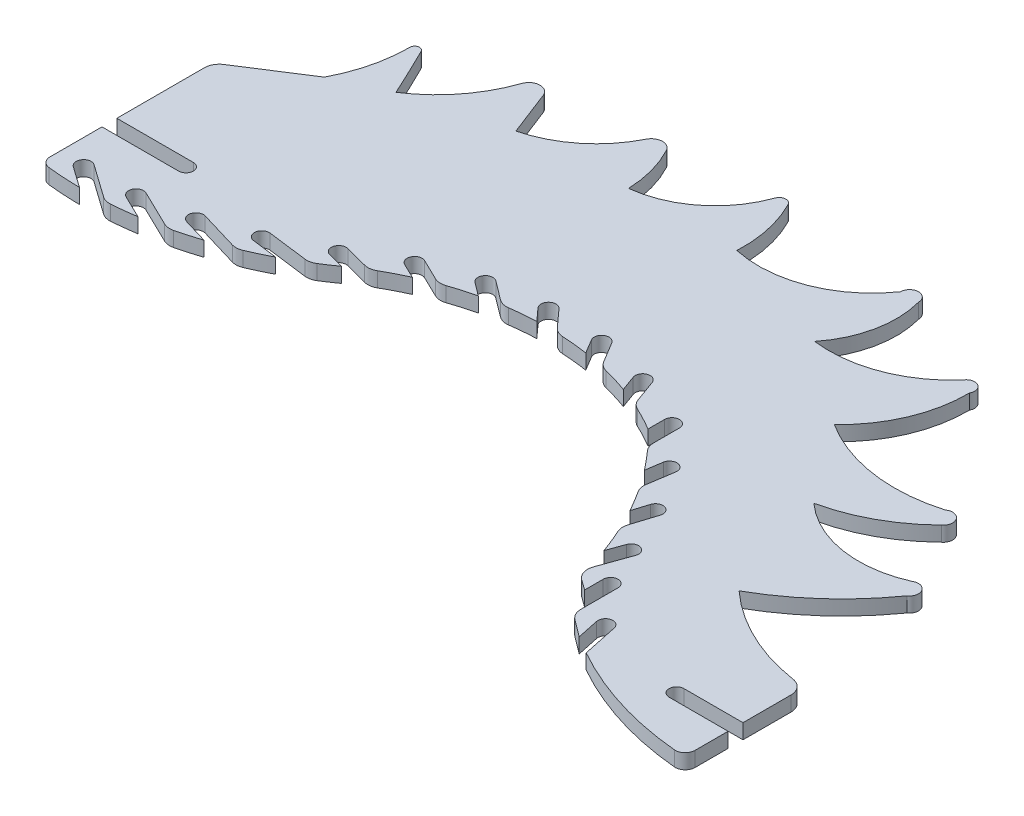
SolidWorks part; units mm, degrees
ref_plane "Front Plane" through (0, 0, 0) normal (0, 0, 1) x (1, 0, 0)
ref_plane "Top Plane" through (0, 0, 0) normal (0, 1, 0) x (1, 0, 0)
ref_plane "Right Plane" through (0, 0, 0) normal (1, 0, 0) x (0, 0, -1)
sketch "Sketch1" plane through (0, 0, 0) normal (0, 1, 0) x (1, 0, 0)
  line L0 (0, 0) -> (-11.9, 0)
  line L1 (-11.9, -3) -> (0, -3)
  line L2 (0, -3) -> (0, -11.81)
  line L3 (0, 0) -> (0, 12.34)
  line L4 (-28, -3.62) -> (-29.5212, 3.5443)
  line L5 (-32.4557, 2.9212) -> (-31.5128, -1.52)
  line L6 (-31.5128, -1.52) -> (-36.1543, 1.95)
  line L7 (-36.1543, 1.95) -> (-36.1543, 10.96)
  line L8 (-39.1543, 10.96) -> (-39.1543, 7.21)
  line L9 (-39.1543, 7.21) -> (-43.0543, 10.02)
  line L10 (-43.0543, 10.02) -> (-40.0457, 18.3911)
  line L11 (-42.8689, 19.4057) -> (-44.0821, 16.03)
  line L12 (-60.88, 41.7175) -> (-60.88, 45.0575)
  line L13 (-57.88, 45.0575) -> (-57.88, 38.6806)
  line L14 (-50.5732, 36.9998) -> (-51.5447, 30.6973)
  line L15 (-54.0471, 34.1558) -> (-53.5382, 37.4568)
  line L16 (-44.5793, 27.923) -> (-46.4997, 21.8421)
  line L17 (-48.4459, 25.6414) -> (-47.4401, 28.8264)
  line L18 (-68.5978, 50.2986) -> (-66.54, 44.6449)
  line L19 (-70.2786, 46.1451) -> (-71.4169, 49.2725)
  line L20 (-80.4271, 48.716) -> (-82.1438, 51.5672)
  line L21 (-79.5737, 53.1147) -> (-76.4703, 47.9603)
  line L22 (-90.8803, 49.2938) -> (-93.1117, 51.7631)
  line L23 (-90.8859, 53.7745) -> (-86.8519, 49.3106)
  line L24 (-101.2503, 47.8571) -> (-103.9137, 49.8528)
  line L25 (-102.1147, 52.2536) -> (-97.2999, 48.6458)
  line L26 (-111.1527, 44.4592) -> (-114.1492, 45.9074)
  line L27 (-112.8438, 48.6085) -> (-107.4267, 45.9905)
  line L28 (-120.22, 39.2261) -> (-123.4386, 40.0729)
  line L29 (-122.6752, 42.9742) -> (-116.8567, 41.4432)
  line L30 (-160.4297, 26.5895) -> (-164.6544, 29.5786)
  line L31 (-162.9217, 32.0276) -> (-155.4197, 26.7198)
  line L32 (-149.4017, 27.3689) -> (-154.0553, 29.6332)
  line L33 (-152.7427, 32.3308) -> (-144.4792, 28.3099)
  line L34 (-138.6461, 29.9265) -> (-143.6054, 31.4061)
  line L35 (-142.7477, 34.2809) -> (-133.9414, 31.6534)
  line L36 (-128.4478, 34.1946) -> (-133.5813, 34.8503)
  line L37 (-133.2012, 37.8261) -> (-124.0854, 36.6617)
  line L38 (-168.7197, 27.1883) -> (-168.7197, 39.4283)
  line L39 (-168.7197, 39.4283) -> (-153.2697, 39.4283)
  line L40 (-153.2697, 42.4283) -> (-168.7197, 42.4283)
  line L41 (-168.7197, 42.4283) -> (-168.7197, 61.7183)
  line L42 (-168.7197, 61.7183) -> (-154.9797, 70.5483)
  line L43 (-129.7315, 89.4454) -> (-126.2359, 80.4346)
  arc A0 (-11.9, 0) -> (-11.9, -3) centre (-11.9, -1.5) ccw
  arc A1 (0, 12.34) -> (-23.42, 22.6266) centre (3.4988, 52.1101) cw
  arc A2 (0, -11.81) -> (-28, -3.62) centre (3.4988, 52.1101) cw
  arc A3 (-29.5212, 3.5443) -> (-32.4557, 2.9212) centre (-30.9885, 3.2327) ccw
  arc A4 (-36.1543, 10.96) -> (-39.1543, 10.96) centre (-37.6543, 10.96) ccw
  arc A5 (-40.0457, 18.3911) -> (-42.8689, 19.4057) centre (-41.4573, 18.8984) ccw
  arc A6 (-120.22, 39.2261) -> (-111.1527, 44.4592) centre (-88.64, -5.02) cw construction
  arc A7 (-44.0821, 16.03) -> (-60.88, 41.7175) centre (-106.8072, -6.6518) ccw construction
  arc A8 (-60.88, 45.0575) -> (-57.88, 45.0575) centre (-59.38, 45.0575) cw
  arc A9 (-53.5382, 37.4568) -> (-50.5732, 36.9998) centre (-52.0557, 37.2283) cw
  arc A10 (-47.4401, 28.8264) -> (-44.5793, 27.923) centre (-46.0097, 28.3747) cw
  arc A11 (-71.4169, 49.2725) -> (-68.5978, 50.2986) centre (-70.0073, 49.7856) cw
  arc A12 (-82.1438, 51.5672) -> (-79.5737, 53.1147) centre (-80.8587, 52.3409) cw
  arc A13 (-93.1117, 51.7631) -> (-90.8859, 53.7745) centre (-91.9988, 52.7688) cw
  arc A14 (-103.9137, 49.8528) -> (-102.1147, 52.2536) centre (-103.0142, 51.0532) cw
  arc A15 (-114.1492, 45.9074) -> (-112.8438, 48.6085) centre (-113.4965, 47.2579) cw
  arc A16 (-123.4386, 40.0729) -> (-122.6752, 42.9742) centre (-123.0569, 41.5236) cw
  arc A17 (-120.22, 39.2261) -> (-124.0854, 36.6617) centre (-159.6892, 94.5255) cw
  arc A18 (-164.6544, 29.5786) -> (-162.9217, 32.0276) centre (-163.7881, 30.8031) cw
  arc A19 (-154.0553, 29.6332) -> (-152.7427, 32.3308) centre (-153.399, 30.982) cw
  arc A20 (-143.6054, 31.4061) -> (-142.7477, 34.2809) centre (-143.1765, 32.8435) cw
  arc A21 (-133.5813, 34.8503) -> (-133.2012, 37.8261) centre (-133.3913, 36.3382) cw
  arc A22 (-153.2697, 39.4283) -> (-153.2697, 42.4283) centre (-153.2697, 40.9283) ccw
  arc A23 (-154.9797, 70.5483) -> (-151.5597, 84.3925) centre (-181.2904, 84.3925) ccw
  arc A24 (-151.5597, 84.3925) -> (-149.7376, 84.8202) centre (-150.5985, 84.3925) cw
  arc A25 (-149.7376, 84.8202) -> (-145.1059, 75.1079) centre (-449.3568, -64.0278) cw
  arc A26 (-145.1059, 75.1079) -> (-133.9563, 89.3652) centre (-160.2375, 98.4295) ccw
  arc A27 (-133.9563, 89.3652) -> (-129.7315, 89.4454) centre (-131.8292, 88.6316) cw
  arc A28 (-126.2359, 80.4346) -> (-111.6812, 92.1765) centre (-131.832, 102.2628) ccw
  arc A29 (-111.6812, 92.1765) -> (-107.6875, 92.235) centre (-109.6692, 91.1694) cw
  arc A30 (-107.6875, 92.235) -> (-104.8659, 81.7843) centre (-128.6278, 80.9749) cw
  arc A31 (-104.8659, 81.7843) -> (-88.4017, 94.8891) centre (-107.1557, 101.5559) ccw
  arc A32 (-88.4017, 94.8891) -> (-85.9569, 95.0539) centre (-87.1436, 94.4419) cw
  arc A33 (-85.9569, 95.0539) -> (-83.1003, 81.8651) centre (-109.0383, 83.1508) cw
  arc A34 (-154.9797, 70.5483) -> (-104.8659, 81.7843) centre (-109.48, -15.0111) cw construction
  arc A35 (-104.8659, 81.7843) -> (-23.42, 22.6266) centre (-93.7218, 11.4825) cw construction
  arc A36 (-83.1003, 81.8651) -> (-59.38, 91.1694) centre (-78.1992, 104.2586) ccw
  arc A37 (-59.38, 91.1694) -> (-55.7555, 91.1694) centre (-57.5677, 91.1694) cw
  arc A38 (-59.38, 73.8297) -> (-37.6543, 82.0653) centre (-56.2688, 98.3966) ccw
  arc A39 (-59.38, 73.8297) -> (-55.7555, 91.1694) centre (-74.6215, 86.0643) ccw
  arc A40 (-37.6543, 82.0653) -> (-34.7502, 80.4346) centre (-36.2022, 81.25) cw
  arc A41 (-34.7502, 80.4346) -> (-42.8689, 61.2873) centre (-60.585, 80.094) cw
  arc A42 (-42.8689, 61.2873) -> (-16.7465, 57.5523) centre (-25.6992, 88.1549) ccw
  arc A43 (-16.7465, 57.5523) -> (-14.519, 54.5175) centre (-15.6327, 56.0349) cw
  arc A44 (-14.519, 54.5175) -> (-31.1784, 45.4656) centre (-38.661, 79.093) cw
  arc A45 (-31.1784, 45.4656) -> (-7.6655, 41.7175) centre (-16.527, 61.752) ccw
  arc A46 (-7.6655, 41.7175) -> (-5.6274, 38.6806) centre (-6.6465, 40.199) cw
  arc A47 (-5.6274, 38.6806) -> (-23.42, 22.6266) centre (-50.457, 70.4782) cw
  arc A48 (-66.54, 44.6449) -> (-60.88, 41.7175) centre (-88.64, -5.02) cw
  arc A49 (-76.4703, 47.9603) -> (-70.2786, 46.1451) centre (-88.64, -5.02) cw
  arc A50 (-86.8519, 49.3106) -> (-80.4271, 48.716) centre (-88.64, -5.02) cw
  arc A51 (-97.2999, 48.6458) -> (-90.8803, 49.2938) centre (-88.64, -5.02) cw
  arc A52 (-107.4267, 45.9905) -> (-101.2503, 47.8571) centre (-88.64, -5.02) cw
  arc A53 (-116.8567, 41.4432) -> (-111.1527, 44.4592) centre (-88.64, -5.02) cw
  arc A54 (-128.4478, 34.1946) -> (-133.9414, 31.6534) centre (-159.6892, 94.5255) cw
  arc A55 (-138.6461, 29.9265) -> (-144.4792, 28.3099) centre (-159.6892, 94.5255) cw
  arc A56 (-149.4017, 27.3689) -> (-155.4197, 26.7198) centre (-159.6892, 94.5255) cw
  arc A57 (-160.4297, 26.5895) -> (-168.7197, 27.1883) centre (-159.6892, 94.5255) cw
  arc A58 (-57.88, 38.6806) -> (-54.0471, 34.1558) centre (-106.8072, -6.6518) cw
  arc A59 (-51.5447, 30.6973) -> (-48.4459, 25.6414) centre (-106.8072, -6.6518) cw
  arc A60 (-46.4997, 21.8421) -> (-44.0821, 16.03) centre (-106.8072, -6.6518) cw
  point P10 (-13.4, -1.5)
  point P13 (-21.53, -6.81)
  point P17 (-31.3, 4.7)
  point P19 (-31.9843, 0.7006)
  point P39 (-40.95, 20.31)
  point P40 (-59.38, 46.5575)
  point P41 (-88.64, -5.02)
  point P62 (-70.5204, 51.1951)
  point P87 (-165.0126, 31.6695)
  point P115 (-151.7697, 40.9283)
  point P116 (-150.8181, 85.3283)
  point P136 (-131.8719, 90.8812)
  point P145 (-109.7021, 93.4192)
  dimension "D3" = 1.5
  dimension "D23" = 54.36
  dimension "D24" = 66.7
  dimension "D35" = 67.94
  dimension "D43" = 16.95
  dimension "D52" = 2.25
  dimension "D48" = 96.9053
  dimension "D53" = 29.7307
  dimension "D56" = 0.9612
  dimension "D57" = 334.5555
  dimension "D58" = 27.8005
  dimension "D59" = 22.5341
  dimension "D60" = 23.7757
  dimension "D61" = 19.9038
  dimension "D62" = 1.3352
  dimension "D63" = 25.9698
  dimension "D64" = 71.1796
  dimension "D65" = 22.9236
  dimension "D66" = 1.8123
  dimension "D67" = 24.7631
  dimension "D68" = 19.5445
  dimension "D69" = 1.6653
  dimension "D70" = 25.837
  dimension "D71" = 31.8852
  dimension "D72" = 1.8823
  dimension "D73" = 34.4498
  dimension "D74" = 21.9068
  dimension "D75" = 1.8287
  dimension "D76" = 54.9615
  dimension "D1" = 24.15
  dimension "D2" = 13.4
  dimension "D4" = 8.19
  dimension "D5" = 28
  dimension "D6" = 21.53
  dimension "D7" = 5
  dimension "D8" = 8.81
  dimension "D9" = 31.3
  dimension "D10" = 16.51
  dimension "D11" = 10.29
  dimension "D12" = 13.76
  dimension "D13" = 4.17
  dimension "D14" = 12.48
  dimension "D15" = 19.02
  dimension "D16" = 3.9
  dimension "D17" = 21.83
  dimension "D18" = 40.95
  dimension "D19" = 13.1
  dimension "D20" = 27.84
  dimension "D21" = 88.64
  dimension "D22" = 6.79
  dimension "D25" = 60.88
  dimension "D26" = 23.42
  dimension "D27" = 4.84
  dimension "D29" = 5.93
  dimension "D30" = 5.66
  dimension "D31" = 20
  dimension "D32" = 5.05
  dimension "D34" = 122.22
  dimension "D36" = 120.22
  dimension "D37" = 8.29
  dimension "D38" = 5.08
  dimension "D39" = 13.3
  dimension "D41" = 6.018
  dimension "D42" = 34.53
  dimension "12.24" = 12.24
  dimension "D44" = 17.16
  dimension "D45" = 28.12
  dimension "D46" = 44.4
  dimension "D47" = 13.74
  dimension "D49" = 18.87
  dimension "D50" = 11.87
  dimension "D51" = 21.37
  dimension "D54" = 46.24
  dimension "D55" = 12.6
  dimension "D77" = 5.6274
  dimension "D78" = 6.6465
  dimension "D79" = 14.519
  dimension "D80" = 15.6327
  dimension "D81" = 16.527
  dimension "D82" = 16.7465
  dimension "D83" = 25.6992
  dimension "D84" = 34.7502
  dimension "D85" = 36.2022
  dimension "D86" = 50.457
  dimension "D87" = 56.2688
  dimension "D88" = 74.6215
  dimension "D89" = 78.1992
  dimension "D90" = 85.9569
  dimension "D91" = 87.1436
  dimension "D92" = 131.8292
  dimension "D28" = 3
  dimension "D33" = 6
  dimension "D40" = 4
extrude "Boss-Extrude1" add sketch "Sketch1" along normal blind 3
fillet "Fillet1" radius 3 1 edges at (0, 1.5, -12.34)
fillet "Fillet2" radius 2 2 edges at (-168.7197, 1.5, -27.1883) (0, 1.5, 11.81)
fillet "Fillet3" radius 3 16 edges at (-155.4197, 1.5, -26.7198) (-144.4792, 1.5, -28.3099) (-133.9414, 1.5, -31.6534) (-124.0854, 1.5, -36.6617) (-116.8567, 1.5, -41.4432) (-107.4267, 1.5, -45.9905) (-97.2999, 1.5, -48.6458) (-86.8519, 1.5, -49.3106) (-76.4703, 1.5, -47.9603) (-66.54, 1.5, -44.6449) (-57.88, 1.5, -38.6806) (-51.5447, 1.5, -30.6973) (-46.4997, 1.5, -21.8421) (-36.1543, 1.5, -1.95) (-43.0543, 1.5, -10.02) (-168.7197, 1.5, -61.7183)
